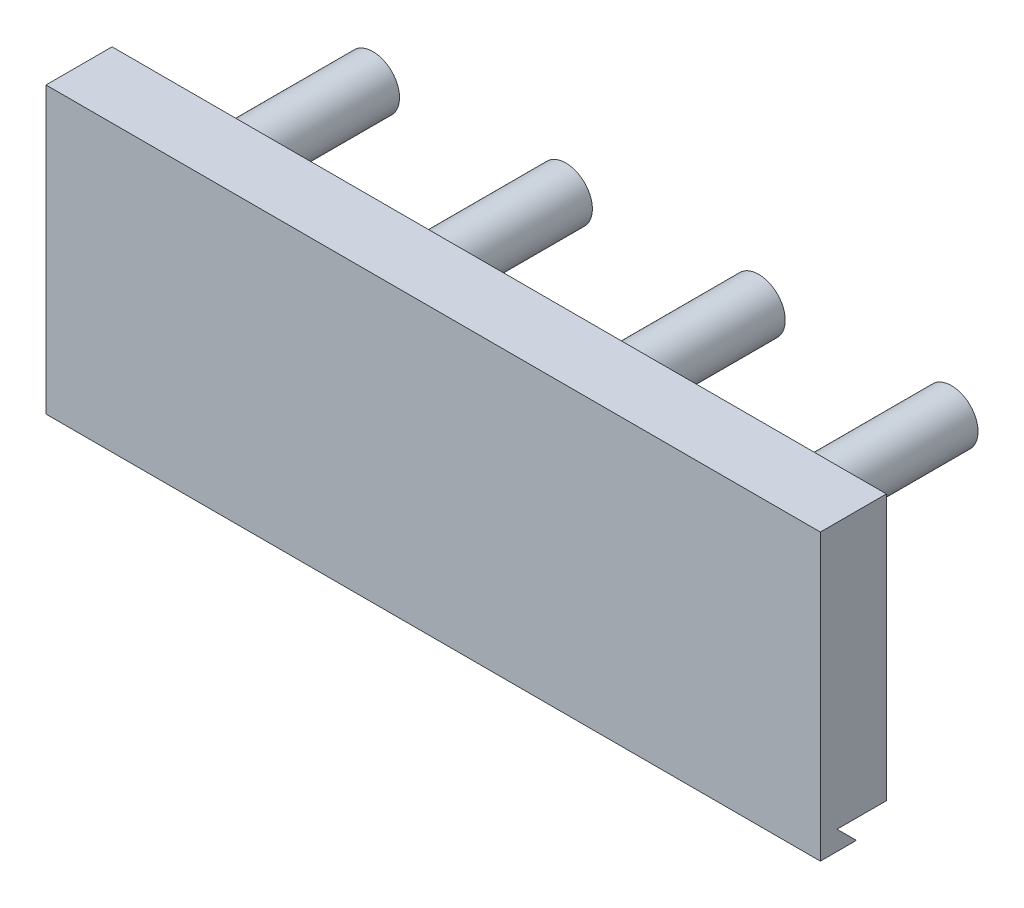
SolidWorks part; units mm, degrees
ref_plane "Front Plane" through (0, 0, 0) normal (0, 0, 1) x (1, 0, 0)
ref_plane "Top Plane" through (0, 0, 0) normal (0, 1, 0) x (1, 0, 0)
ref_plane "Right Plane" through (0, 0, 0) normal (1, 0, 0) x (0, 0, -1)
sketch "Sketch1" plane through (0, 0, 0) normal (0, 0, 1) x (1, 0, 0)
  line L1 (-51, -17.5) -> (51, -17.5)
  line L2 (-51, -17.5) -> (-51, 17.5)
  line L3 (-51, 17.5) -> (51, 17.5)
  line L4 (51, -17.5) -> (51, 17.5)
  line L5 (-51, -17.5) -> (51, 17.5) construction
  line L6 (-51, 17.5) -> (51, -17.5) construction
  point P0 (0, 0)
  dimension "D1" = 35
  dimension "D2" = 102
extrude "Boss-Extrude1" add sketch "Sketch1" along normal blind 8.7
sketch "Sketch4" plane through (-51, 0, 0) normal (-1, 0, 0) x (0, 0, 1)
  line L2 (6.5, -17.5) -> (8.7, -17.5)
  line L6 (8.7, -17.5) -> (8.7, -20.0456)
  line L12 (8.7, -20.0456) -> (3.9544, -20.0456)
  line L13 (3.9544, -20.0456) -> (6.5, -17.5)
  line L14 (8.7, -17.5) -> (0, -17.5) construction
  dimension "D1" = 6.5
  dimension "D2" = 45
  dimension "D3" = 3.6
extrude "Boss-Extrude2" add sketch "Sketch4" against normal blind 102
sketch "Sketch5" plane through (0, 0, 0) normal (0, 0, -1) x (-1, 0, 0)
  line L0 (51, -17.5) -> (-51, -17.5) construction
  line L2 (51, 17.5) -> (51, -17.5) construction
  circle A0 centre (-39.57, 10.64) radius 3.5
  circle A1 centre (-14.17, 10.64) radius 3.5
  circle A2 centre (11.23, 10.64) radius 3.5
  circle A3 centre (36.63, 10.64) radius 3.5
  dimension "D2" = 7
  dimension "D7" = 7
  dimension "D8" = 7
  dimension "D9" = 7
  dimension "D1" = 28.14
  dimension "D3" = 14.37
  dimension "D4" = 25.4
  dimension "D5" = 25.4
  dimension "D6" = 25.4
  dimension "D10" = 28.14
  dimension "D11" = 28.14
  dimension "D12" = 28.14
extrude "Boss-Extrude3" add sketch "Sketch5" along normal blind 20
